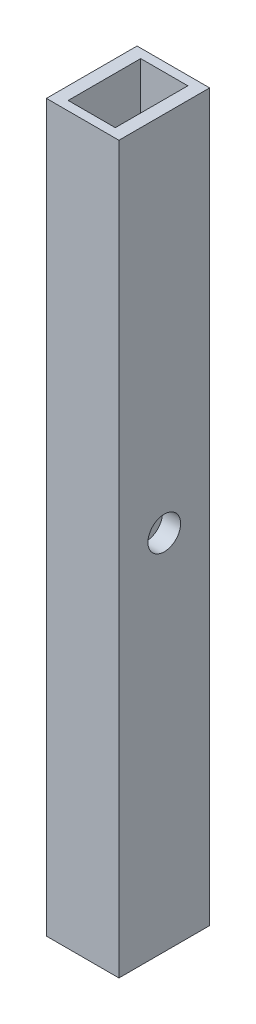
SolidWorks part; units mm, degrees
ref_plane "Front Plane" through (0, 0, 0) normal (0, 0, 1) x (1, 0, 0)
ref_plane "Top Plane" through (0, 0, 0) normal (0, 1, 0) x (1, 0, 0)
ref_plane "Right Plane" through (0, 0, 0) normal (1, 0, 0) x (0, 0, -1)
sketch "Sketch1" plane through (0, 0, 0) normal (0, 1, 0) x (1, 0, 0)
  line L1 (-50, 62.5) -> (50, 62.5)
  line L2 (-50, 62.5) -> (-50, -62.5)
  line L3 (-50, -62.5) -> (50, -62.5)
  line L4 (50, 62.5) -> (50, -62.5)
  line L5 (-50, 62.5) -> (50, -62.5) construction
  line L6 (-50, -62.5) -> (50, 62.5) construction
  point P0 (0, 0)
  dimension "D1" = 125
  dimension "D2" = 100
extrude "Boss-Extrude1" add sketch "Sketch1" along normal mid plane 1000
sketch "Sketch2" plane through (50, 0, 0) normal (1, 0, 0) x (0, 0, -1)
  line L0 (-228.7534, 0) -> (255.6656, 0) construction
  circle A0 centre (0, 0) radius 22.5
  dimension "D1" = 45
extrude "Cut-Extrude1" cut sketch "Sketch2" against normal blind 25
sketch "Sketch3" plane through (-50, 0, 0) normal (-1, 0, 0) x (0, 0, 1)
  circle A0 centre (0, 0) radius 22.5
  dimension "D1" = 45
extrude "Cut-Extrude2" cut sketch "Sketch3" against normal blind 25
sketch "Sketch4" plane through (0, 500, 0) normal (0, 1, 0) x (1, 0, 0)
  line L0 (50, 62.5) -> (-50, 62.5) construction
  line L1 (-32.5, 50) -> (32.5, 50)
  line L2 (-32.5, 50) -> (-32.5, -50)
  line L3 (-32.5, -50) -> (32.5, -50)
  line L4 (32.5, 50) -> (32.5, -50)
  line L5 (-32.5, 50) -> (32.5, -50) construction
  line L6 (-32.5, -50) -> (32.5, 50) construction
  point P0 (0, 0)
  dimension "D1" = 65
  dimension "D2" = 100
  dimension "D3" = 12.5
extrude "Cut-Extrude3" cut sketch "Sketch4" against normal blind 400
